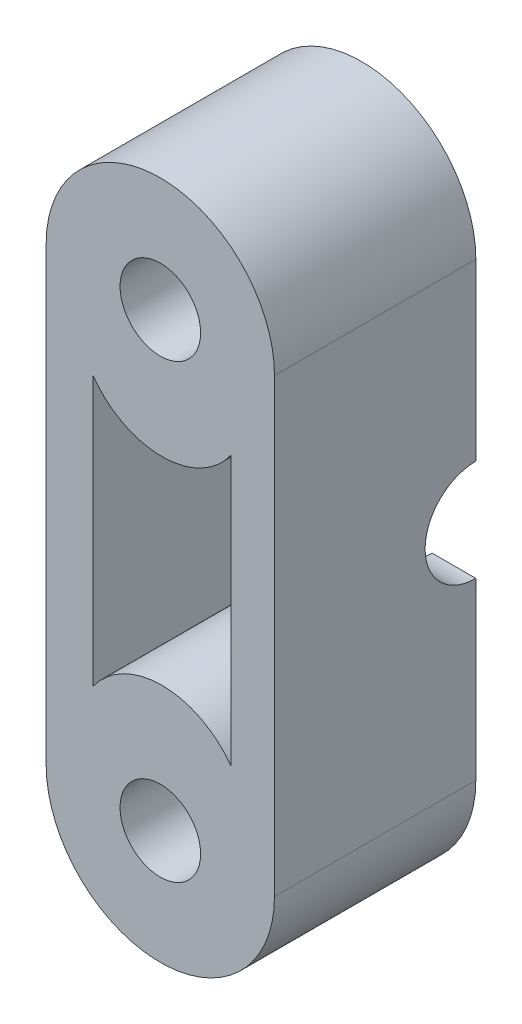
SolidWorks part; units mm, degrees
ref_plane "Plan de face" through (0, 0, 0) normal (0, 0, 1) x (1, 0, 0)
ref_plane "Plan de dessus" through (0, 0, 0) normal (0, 1, 0) x (1, 0, 0)
ref_plane "Plan de droite" through (0, 0, 0) normal (1, 0, 0) x (0, 0, -1)
sketch "Esquisse1" plane through (0, 0, 0) normal (0, 0, 1) x (1, 0, 0)
  line L0 (-25.3716, 59.9165) -> (-22.7576, 59.9165) construction
  line L2 (-30.2062, 71.1203) -> (-30.2062, 59.9165)
  line L4 (-24.537, 71.1203) -> (-24.537, 59.9165)
  line L5 (-29.0389, 68.8624) -> (-29.0389, 62.1905)
  line L7 (-25.6216, 68.8624) -> (-25.6216, 62.1905)
  arc A0 (-24.537, 71.1203) -> (-30.2062, 71.1203) centre (-27.3716, 71.1203) ccw
  arc A1 (-30.2062, 59.9165) -> (-24.537, 59.9165) centre (-27.3716, 59.9165) ccw
  circle A2 centre (-27.3716, 71.1203) radius 2 construction
  circle A3 centre (-27.3716, 59.9165) radius 2 construction
  circle A4 centre (-27.3716, 59.9165) radius 1 construction
  circle A5 centre (-27.3716, 71.1203) radius 1 construction
  circle A6 centre (-27.3716, 59.9165) radius 1
  circle A7 centre (-27.3716, 71.1203) radius 1
  arc A8 (-29.0389, 68.8624) -> (-25.6216, 68.8624) centre (-27.3302, 70.0761) ccw
  arc A9 (-29.0389, 62.1905) -> (-25.6216, 62.1905) centre (-27.3302, 60.9531) cw
extrude "Extrusion1" add sketch "Esquisse1" along normal blind 5
sketch "Esquisse2" plane through (-24.537, 0, 0) normal (1, 0, 0) x (0, 0, -1)
  circle A0 centre (0, 65.5184) radius 1.26
extrude "Enlèv. mat.-Extru.1" cut sketch "Esquisse2" against normal blind 15
sketch "Esquisse3" plane through (0, 0, 0) normal (0, 0, -1) x (-1, 0, 0)
  line L2 (26.3716, 59.9165) -> (28.3716, 59.9165) construction
  circle A0 centre (27.3716, 71.1203) radius 2
  circle A1 centre (27.3716, 59.9165) radius 2
  dimension "D1" = 4
  dimension "D2" = 4
extrude "Enlèv. mat.-Extru.2" cut sketch "Esquisse3" against normal blind 3
